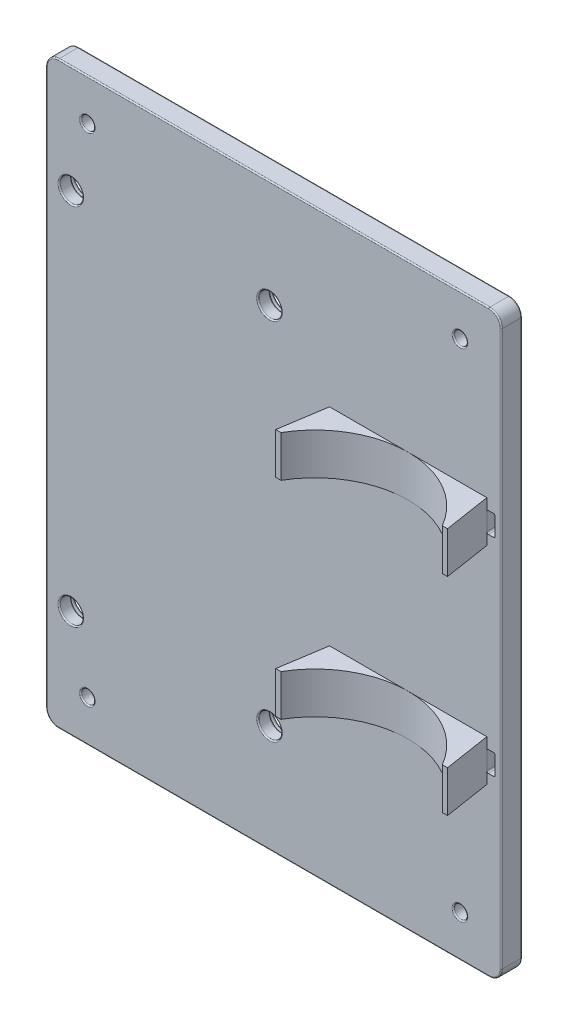
SolidWorks part; units mm, degrees
ref_plane "Front Plane" through (0, 0, 0) normal (0, 0, 1) x (1, 0, 0)
ref_plane "Top Plane" through (0, 0, 0) normal (0, 1, 0) x (1, 0, 0)
ref_plane "Right Plane" through (0, 0, 0) normal (1, 0, 0) x (0, 0, -1)
sketch "Sketch1" plane through (0, 0, 0) normal (0, 0, 1) x (1, 0, 0)
  line L0 (106.5, 97.1) -> (106.5, 92.9)
  line L1 (3, 0) -> (107, 0)
  line L2 (0, 3) -> (0, 137)
  line L3 (3, 140) -> (107, 140)
  line L4 (110, 3) -> (110, 137)
  line L5 (106.9, 97.5) -> (108.1, 97.5)
  line L15 (106.9, 92.5) -> (108.1, 92.5)
  line L16 (108.5, 97.1) -> (108.5, 92.9)
  line L17 (106.5, 47.1) -> (106.5, 42.9)
  line L19 (106.9, 47.5) -> (108.1, 47.5)
  line L20 (106.9, 42.5) -> (108.1, 42.5)
  line L21 (108.5, 47.1) -> (108.5, 42.9)
  line L22 (66.5, 47.1) -> (66.5, 42.9)
  line L23 (66.9, 47.5) -> (68.1, 47.5)
  line L24 (66.9, 42.5) -> (68.1, 42.5)
  line L25 (68.5, 47.1) -> (68.5, 42.9)
  line L26 (66.5, 97.1) -> (66.5, 92.9)
  line L27 (66.9, 97.5) -> (68.1, 97.5)
  line L28 (66.9, 92.5) -> (68.1, 92.5)
  line L29 (68.5, 97.1) -> (68.5, 92.9)
  arc A0 (107, 0) -> (110, 3) centre (107, 3) ccw
  arc A1 (107, 140) -> (110, 137) centre (107, 137) cw
  arc A2 (0, 137) -> (3, 140) centre (3, 137) cw
  arc A3 (3, 0) -> (0, 3) centre (3, 3) cw
  circle A4 centre (6, 26) radius 2.8
  circle A5 centre (54, 26) radius 2.8
  circle A6 centre (54, 114) radius 2.8
  circle A7 centre (6, 114) radius 2.8
  circle A8 centre (10, 130) radius 1.6
  circle A9 centre (100, 130) radius 1.6
  circle A10 centre (10, 10) radius 1.6
  circle A11 centre (100, 10) radius 1.6
  arc A12 (106.5, 97.1) -> (106.9, 97.5) centre (106.9, 97.1) cw
  arc A13 (106.5, 92.9) -> (106.9, 92.5) centre (106.9, 92.9) ccw
  arc A14 (108.1, 97.5) -> (108.5, 97.1) centre (108.1, 97.1) cw
  arc A15 (108.5, 92.9) -> (108.1, 92.5) centre (108.1, 92.9) cw
  arc A16 (106.5, 47.1) -> (106.9, 47.5) centre (106.9, 47.1) cw
  arc A17 (106.5, 42.9) -> (106.9, 42.5) centre (106.9, 42.9) ccw
  arc A18 (108.1, 47.5) -> (108.5, 47.1) centre (108.1, 47.1) cw
  arc A19 (108.5, 42.9) -> (108.1, 42.5) centre (108.1, 42.9) cw
  arc A20 (66.5, 47.1) -> (66.9, 47.5) centre (66.9, 47.1) cw
  arc A21 (66.5, 42.9) -> (66.9, 42.5) centre (66.9, 42.9) ccw
  arc A22 (68.1, 47.5) -> (68.5, 47.1) centre (68.1, 47.1) cw
  arc A23 (68.5, 42.9) -> (68.1, 42.5) centre (68.1, 42.9) cw
  arc A24 (66.5, 97.1) -> (66.9, 97.5) centre (66.9, 97.1) cw
  arc A25 (66.5, 92.9) -> (66.9, 92.5) centre (66.9, 92.9) ccw
  arc A26 (68.1, 97.5) -> (68.5, 97.1) centre (68.1, 97.1) cw
  arc A27 (68.5, 92.9) -> (68.1, 92.5) centre (68.1, 92.9) cw
extrude "Boss-Extrude1" add sketch "Sketch1" along normal blind 5
sketch "Sketch2" plane through (0, 0, 0) normal (0, 0, -1) x (-1, 0, 0)
  line L1 (-108.1191, 97.5) -> (-66.9, 97.5)
  line L2 (-108.5191, 97.1) -> (-108.5191, 92.9)
  line L3 (-108.1191, 92.5) -> (-66.9, 92.5)
  line L4 (-66.5, 97.1) -> (-66.5, 92.9)
  line L5 (-108.1, 47.5) -> (-66.9, 47.5)
  line L6 (-108.5, 47.1) -> (-108.5, 42.9)
  line L7 (-108.1, 42.5) -> (-66.9, 42.5)
  line L8 (-66.5, 47.1) -> (-66.5, 42.9)
  circle A0 centre (-54, 114) radius 4.5
  circle A1 centre (-54, 26) radius 4.5
  circle A2 centre (-6, 26) radius 4.5
  circle A3 centre (-6, 114) radius 4.5
  arc A4 (-66.9, 92.5) -> (-66.5, 92.9) centre (-66.9, 92.9) ccw
  arc A5 (-66.9, 97.5) -> (-66.5, 97.1) centre (-66.9, 97.1) cw
  arc A6 (-108.1191, 97.5) -> (-108.5191, 97.1) centre (-108.1191, 97.1) ccw
  arc A7 (-108.5191, 92.9) -> (-108.1191, 92.5) centre (-108.1191, 92.9) ccw
  arc A8 (-66.9, 47.5) -> (-66.5, 47.1) centre (-66.9, 47.1) cw
  arc A9 (-108.1, 47.5) -> (-108.5, 47.1) centre (-108.1, 47.1) ccw
  arc A10 (-108.5, 42.9) -> (-108.1, 42.5) centre (-108.1, 42.9) ccw
  arc A11 (-66.9, 42.5) -> (-66.5, 42.9) centre (-66.9, 42.9) ccw
  dimension "D1" = 0.4
extrude "Cut-Extrude1" cut sketch "Sketch2" against normal blind 2
sketch "Sketch3" plane through (0, 0, 5) normal (0, 0, 1) x (1, 0, 0)
  line L1 (110, 3) -> (110, 137) construction
  line L4 (110, 40) -> (65, 40)
  line L5 (110, 90) -> (65, 90)
  line L6 (110, 90) -> (110, 100)
  line L7 (110, 100) -> (65, 100)
  line L8 (65, 90) -> (65, 100)
  line L13 (110, 40) -> (110, 50)
  line L14 (110, 50) -> (65, 50)
  line L15 (65, 40) -> (65, 50)
extrude "Boss-Extrude2" add sketch "Sketch3" along normal blind 22.5
sketch "Sketch4" plane through (0, 40, 0) normal (0, -1, 0) x (1, 0, 0)
  line L3 (66.75, 16.25) -> (68.0144, 16.25)
  line L6 (68.5, 5) -> (66.75, 16.25)
  line L7 (106.5, 5) -> (108.25, 16.25)
  line L8 (106.9856, 16.25) -> (108.25, 16.25)
  line L9 (68.5, 5) -> (65, 5)
  line L10 (65, 5) -> (65, 27.5)
  line L11 (65, 27.5) -> (110, 27.5)
  line L12 (110, 27.5) -> (110, 5)
  line L13 (110, 5) -> (106.5, 5)
  arc A0 (68.0144, 16.25) -> (106.9856, 16.25) centre (87.5, 27.5) ccw
extrude "Cut-Extrude2" cut sketch "Sketch4" against normal up to surface (60 mm away) up to face at (87.5, 100, 16.25)
fillet "Fillet1" radius 0.3 52 edges at (109.1213, 139.1213, 0) (109.1213, 139.1213, 5) (110, 70, 5) (110, 70, 0) (109.1213, 0.8787, 0) (109.1213, 0.8787, 5) (55, 0, 0) (55, 0, 5) (0.8787, 0.8787, 0) (0.8787, 0.8787, 5) (0, 70, 0) (0, 70, 5) (0.8787, 139.1213, 0) (0.8787, 139.1213, 5) (108.402, 97.3828, 0) (108.5191, 95, 0) (108.402, 92.6172, 0) (87.5096, 92.5, 0) (66.6172, 92.6172, 0) (66.5, 95, 0) (66.6172, 97.3828, 0) (108.3828, 47.3828, 0) (108.5, 45, 0) (108.3828, 42.6172, 0) (87.5, 42.5, 0) (66.6172, 42.6172, 0) (66.5, 45, 0) (66.6172, 47.3828, 0) (55, 140, 0) (55, 140, 5) (11.6, 130, 5) (11.6, 130, 0) (101.6, 130, 5) (101.6, 130, 0) (101.6, 10, 5) (101.6, 10, 0) (11.6, 10, 5) (11.6, 10, 0) (87.5096, 97.5, 0) (56.8, 114, 5) (51.2, 114, 2) (49.5, 114, 0) (87.5, 47.5, 0) (56.8, 26, 5) (51.2, 26, 2) (49.5, 26, 0) (8.8, 26, 5) (3.2, 26, 2) (1.5, 26, 0) (8.8, 114, 5) (3.2, 114, 2) (1.5, 114, 0)
